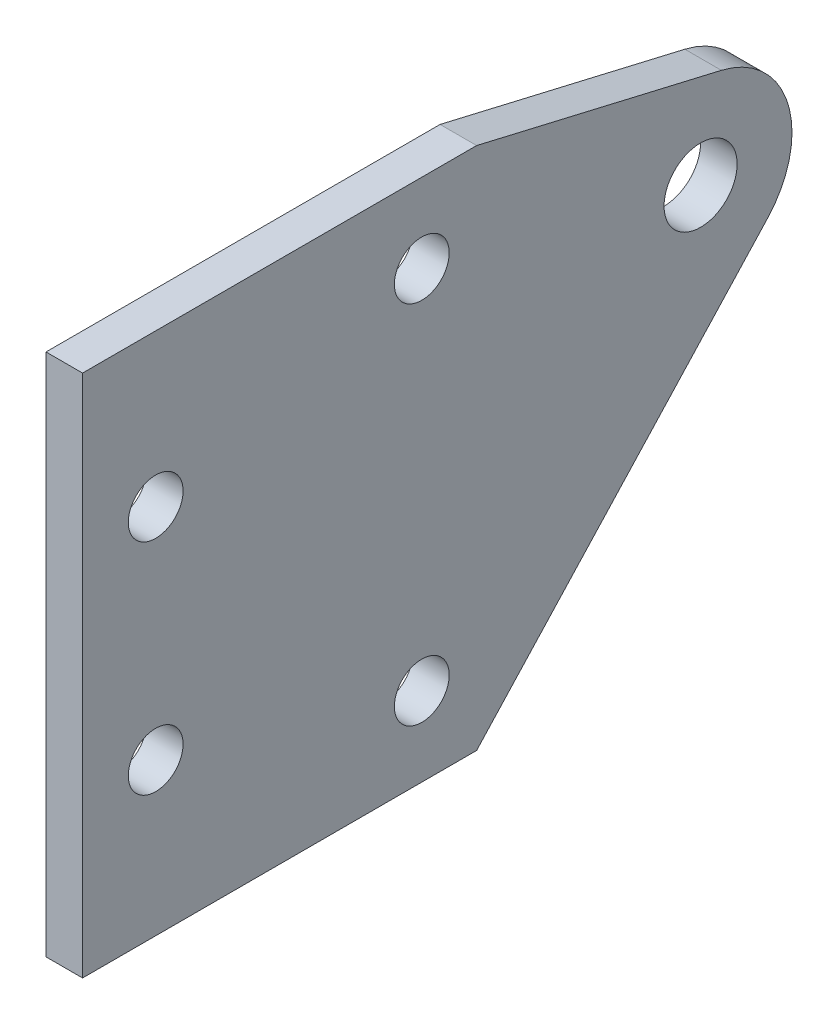
SolidWorks part; units mm, degrees
ref_plane "Front Plane" through (0, 0, 0) normal (0, 0, 1) x (1, 0, 0)
ref_plane "Top Plane" through (0, 0, 0) normal (0, 1, 0) x (1, 0, 0)
ref_plane "Right Plane" through (0, 0, 0) normal (1, 0, 0) x (0, 0, -1)
sketch "Sketch1" plane through (-25.4, 0, 0) normal (-1, 0, 0) x (0, 0, 1)
  line L26 (-54.275, 379.3607) -> (-88.4975, 379.3607)
  line L27 (-88.4975, 379.3607) -> (-109.7572, 374.3897)
  line L28 (-113.7849, 361.2794) -> (-88.4975, 333.8607)
  line L29 (-88.4975, 333.8607) -> (-54.275, 333.8607)
  line L30 (-54.275, 333.8607) -> (-54.275, 379.3607)
  line L31 (-54.275, 379.3607) -> (-88.4975, 379.3607)
  line L32 (-88.4975, 379.3607) -> (-109.7572, 374.3897)
  line L33 (-113.7849, 361.2794) -> (-88.4975, 333.8607)
  line L34 (-88.4975, 333.8607) -> (-54.275, 333.8607)
  line L35 (-54.275, 333.8607) -> (-54.275, 379.3607)
  circle A1 centre (-83.735, 372.4857) radius 2.3813 construction
  circle A2 centre (-83.735, 340.7357) radius 2.3813 construction
  circle A3 centre (-60.625, 366.1357) radius 2.3813 construction
  circle A4 centre (-60.625, 347.0857) radius 2.3813 construction
  circle A6 centre (-83.735, 372.4857) radius 2.3813
  circle A7 centre (-83.735, 340.7357) radius 2.3813
  circle A8 centre (-60.625, 366.1357) radius 2.3813
  circle A9 centre (-60.625, 347.0857) radius 2.3813
  circle A13 centre (-107.95, 366.6607) radius 3.175
  circle A14 centre (-107.95, 366.6607) radius 3.175
  arc A15 (-109.7572, 374.3897) -> (-113.7849, 361.2794) centre (-107.95, 366.6607) ccw
  arc A16 (-109.7572, 374.3897) -> (-113.7849, 361.2794) centre (-107.95, 366.6607) ccw
  dimension "D1" = 0
  dimension "D2" = 0
extrude "Boss-Extrude1" add sketch "Sketch1" along normal blind 3.175
